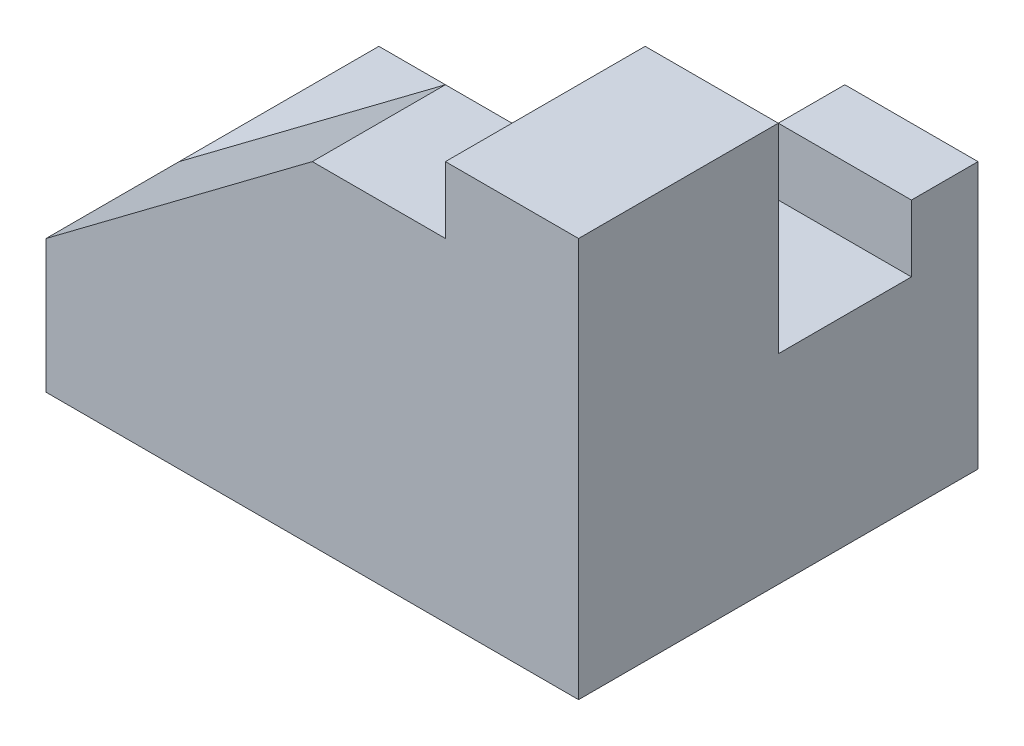
SolidWorks part; units mm, degrees
ref_plane "Alzado" through (0, 0, 0) normal (0, 0, 1) x (1, 0, 0)
ref_plane "Planta" through (0, 0, 0) normal (0, 1, 0) x (1, 0, 0)
ref_plane "Vista lateral" through (0, 0, 0) normal (1, 0, 0) x (0, 0, -1)
sketch "Croquis2" plane through (0, 0, 0) normal (1, 0, 0) x (0, 0, -1)
  line L0 (-545.9227, 0) -> (545.9227, 0) construction
  line L1 (-300, -300) -> (300, -300)
  line L2 (-300, -300) -> (-300, 300)
  line L3 (-300, 300) -> (0, 300)
  line L4 (300, -300) -> (300, 0)
  line L5 (-300, -300) -> (300, 300) construction
  line L6 (-300, 300) -> (300, -300) construction
  line L7 (0, 495.7082) -> (0, -547.2103) construction
  line L8 (0, 300) -> (0, 0)
  line L9 (0, 0) -> (200, 0)
  line L10 (300, 0) -> (300, 100)
  line L11 (300, 100) -> (200, 100)
  line L12 (200, 100) -> (200, 0)
  point P0 (0, 0)
  dimension "D1" = 600
  dimension "D2" = 600
  dimension "D3" = 100
extrude "Saliente-Extruir1" add sketch "Croquis2" along normal blind 200 contours L1 L4 L10 L11 L12 L9 L8 L3 L2
sketch "Croquis3" plane through (0, 0, 0) normal (-1, 0, 0) x (0, 0, 1)
  line L0 (300, -300) -> (300, 300) construction
  line L1 (-300, -300) -> (300, -300)
  line L2 (-300, -300) -> (-300, -100)
  line L3 (-300, -100) -> (300, -100)
  line L4 (300, -300) -> (300, -100)
  dimension "D1" = 200
extrude "Saliente-Extruir2" add sketch "Croquis3" along normal blind 600
sketch "Croquis4" plane through (0, -100, 0) normal (0, 1, 0) x (1, 0, 0)
  line L0 (-600, 200) -> (0, 200)
  line L1 (-600, -300) -> (-600, 300) construction
  line L2 (0, -300) -> (0, 300) construction
  line L3 (0, 200) -> (0, 300)
  line L4 (-600, 300) -> (-600, 200)
  line L5 (0, 300) -> (-600, 300)
  dimension "D1" = 100
extrude "Cortar-Extruir1" cut sketch "Croquis4" against normal up to next
sketch "Croquis5" plane through (0, -100, 0) normal (0, 1, 0) x (1, 0, 0)
  line L0 (-600, 0) -> (-300, 0) construction
  line L1 (-600, -300) -> (-600, 200) construction
  line L2 (-300, 0) -> (-300, 200) construction
  line L3 (-600, 200) -> (0, 200) construction
  line L4 (-500, 200) -> (-100, 200)
  arc A0 (-100, 200) -> (-500, 200) centre (-300, 200) cw
  dimension "D3" = 200
  dimension "D1" = 200
  dimension "D2" = 300
extrude "Cortar-Extruir2" cut sketch "Croquis5" against normal up to next
sketch "Croquis6" plane through (0, -100, 0) normal (0, 1, 0) x (1, 0, 0)
  line L0 (0, -300) -> (0, 0) construction
  line L1 (-600, -300) -> (0, -300)
  line L2 (-600, -300) -> (-600, -100)
  line L3 (-600, -100) -> (0, -100)
  line L4 (0, -300) -> (0, -100)
  dimension "D1" = 200
extrude "Saliente-Extruir3" add sketch "Croquis6" along normal blind 300
sketch "Croquis7" plane through (0, 0, 100) normal (0, 0, -1) x (-1, 0, 0)
  line L0 (0, 200) -> (200, 200) construction
  line L1 (0, 200) -> (600, 200) construction
  line L2 (200, 200) -> (600, -100)
  line L3 (600, -100) -> (600, 200)
  line L4 (600, 200) -> (200, 200)
  dimension "D1" = 200
extrude "Cortar-Extruir3" cut sketch "Croquis7" against normal blind 200
